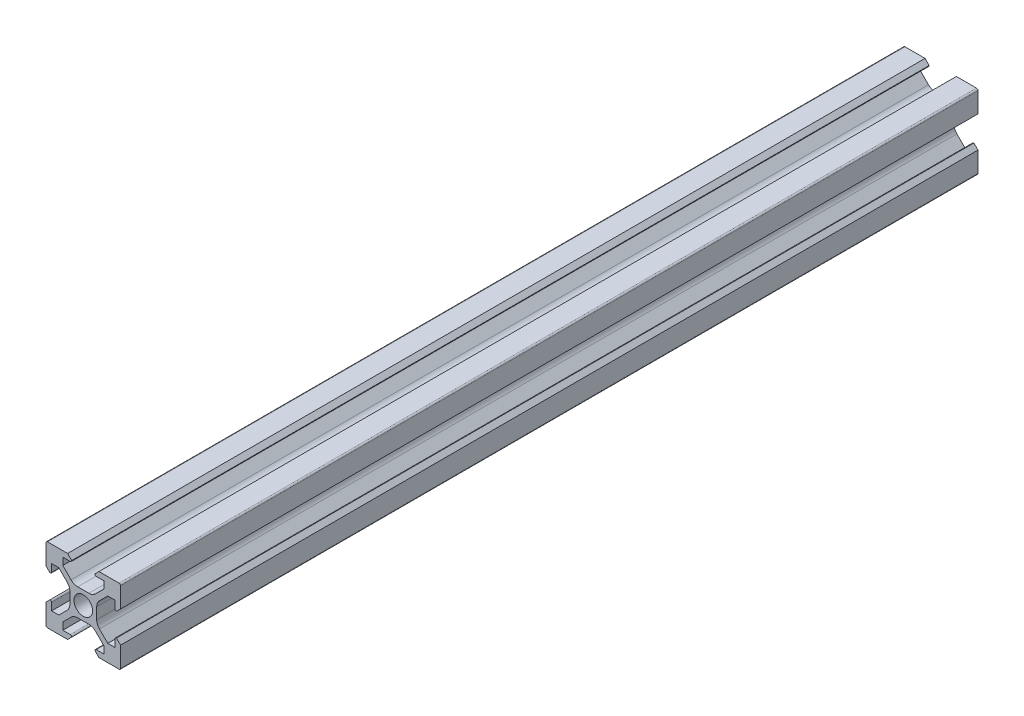
SolidWorks part; units mm, degrees
ref_plane "Plan de face" through (0, 0, 0) normal (0, 0, 1) x (1, 0, 0)
ref_plane "Plan de dessus" through (0, 0, 0) normal (0, 1, 0) x (1, 0, 0)
ref_plane "Plan de droite" through (0, 0, 0) normal (1, 0, 0) x (0, 0, -1)
sketch "Esquisse1" plane through (0, 0, 0) normal (0, 0, 1) x (1, 0, 0)
  line L0 (-3.1, 8.9) -> (-4.2, 10)
  line L1 (-9.6, 10) -> (-4.2, 10)
  line L2 (-3.6, 1.5038) -> (-3.6, 0)
  line L3 (-8.5, 5.5) -> (-8.5, 3.5)
  line L4 (-6.5607, 5.5) -> (-4.3322, 3.2716)
  line L5 (-8.5, 5.5) -> (-6.5607, 5.5)
  line L6 (-10, 9.6) -> (-10, 4.2)
  line L7 (-8.9, 3.1) -> (-10, 4.2)
  line L8 (0, 3.6) -> (0, -3.6) construction
  line L9 (9.8828, -9.8828) -> (0, 0) construction
  line L10 (9.8828, 9.8828) -> (0, 0) construction
  line L11 (3.6, -1.5038) -> (3.6, 0)
  line L12 (8.5, -5.5) -> (8.5, -3.5)
  line L13 (-5.5, 8.5) -> (-5.5, 6.5607)
  line L14 (6.5607, -5.5) -> (4.3322, -3.2716)
  line L15 (8.5, -5.5) -> (6.5607, -5.5)
  line L16 (3.1, -8.9) -> (4.2, -10)
  line L17 (9.6, -10) -> (4.2, -10)
  line L18 (5.5, -8.5) -> (5.5, -6.5607)
  line L19 (5.5, -6.5607) -> (3.2716, -4.3322)
  line L20 (5.5, -8.5) -> (3.5, -8.5)
  line L21 (10, -9.6) -> (10, -4.2)
  line L22 (-9.8828, 9.8828) -> (0, 0) construction
  line L23 (8.9, -3.1) -> (10, -4.2)
  line L24 (-5.5, 6.5607) -> (-3.2716, 4.3322)
  line L25 (5.5, 8.5) -> (3.5, 8.5)
  line L26 (5.5, 6.5607) -> (3.2716, 4.3322)
  line L27 (5.5, 8.5) -> (5.5, 6.5607)
  line L28 (8.9, 3.1) -> (10, 4.2)
  line L29 (10, 9.6) -> (10, 4.2)
  line L30 (8.5, 5.5) -> (6.5607, 5.5)
  line L31 (-5.5, 8.5) -> (-3.5, 8.5)
  line L32 (6.5607, 5.5) -> (4.3322, 3.2716)
  line L33 (8.5, 5.5) -> (8.5, 3.5)
  line L34 (3.6, 1.5038) -> (3.6, 0)
  line L35 (9.6, 10) -> (4.2, 10)
  line L36 (-1.5038, 3.6) -> (1.5038, 3.6)
  line L37 (3.1, 8.9) -> (4.2, 10)
  line L38 (-8.9, -3.1) -> (-10, -4.2)
  line L39 (-10, -9.6) -> (-10, -4.2)
  line L40 (-1.5038, -3.6) -> (1.5038, -3.6)
  line L41 (-5.5, -8.5) -> (-3.5, -8.5)
  line L42 (-5.5, -6.5607) -> (-3.2716, -4.3322)
  line L43 (-5.5, -8.5) -> (-5.5, -6.5607)
  line L44 (-9.6, -10) -> (-4.2, -10)
  line L45 (-3.1, -8.9) -> (-4.2, -10)
  line L46 (-8.5, -5.5) -> (-6.5607, -5.5)
  line L47 (-6.5607, -5.5) -> (-4.3322, -3.2716)
  line L48 (-8.5, -5.5) -> (-8.5, -3.5)
  line L49 (-3.6, -1.5038) -> (-3.6, 0)
  line L50 (-9.8828, -9.8828) -> (0, 0) construction
  arc A0 (2.5, 0) -> (-2.5, 0) centre (0, 0) ccw
  arc A1 (-3.5, 8.5) -> (-3.1, 8.9) centre (-3.5, 8.9) ccw
  arc A2 (-9.6, 10) -> (-10, 9.6) centre (-9.6, 9.6) ccw
  arc A3 (-3.2716, 4.3322) -> (-1.5038, 3.6) centre (-1.5038, 6.1) ccw
  arc A4 (-4.3322, 3.2716) -> (-3.6, 1.5038) centre (-6.1, 1.5038) cw
  arc A5 (-8.5, 3.5) -> (-8.9, 3.1) centre (-8.9, 3.5) cw
  arc A6 (3.5, -8.5) -> (3.1, -8.9) centre (3.5, -8.9) ccw
  arc A7 (3.2716, -4.3322) -> (1.5038, -3.6) centre (1.5038, -6.1) ccw
  arc A8 (4.3322, -3.2716) -> (3.6, -1.5038) centre (6.1, -1.5038) cw
  arc A9 (10, -9.6) -> (9.6, -10) centre (9.6, -9.6) cw
  arc A10 (8.5, -3.5) -> (8.9, -3.1) centre (8.9, -3.5) cw
  arc A11 (8.5, 3.5) -> (8.9, 3.1) centre (8.9, 3.5) ccw
  arc A12 (4.3322, 3.2716) -> (3.6, 1.5038) centre (6.1, 1.5038) ccw
  arc A13 (3.2716, 4.3322) -> (1.5038, 3.6) centre (1.5038, 6.1) cw
  arc A14 (9.6, 10) -> (10, 9.6) centre (9.6, 9.6) cw
  arc A15 (3.5, 8.5) -> (3.1, 8.9) centre (3.5, 8.9) cw
  arc A16 (-2.5, 0) -> (2.5, 0) centre (0, 0) ccw
  arc A17 (-8.5, -3.5) -> (-8.9, -3.1) centre (-8.9, -3.5) ccw
  arc A18 (-10, -9.6) -> (-9.6, -10) centre (-9.6, -9.6) ccw
  arc A19 (-4.3322, -3.2716) -> (-3.6, -1.5038) centre (-6.1, -1.5038) ccw
  arc A20 (-3.2716, -4.3322) -> (-1.5038, -3.6) centre (-1.5038, -6.1) cw
  arc A21 (-3.5, -8.5) -> (-3.1, -8.9) centre (-3.5, -8.9) cw
  point P95 (0, 0)
  dimension "D2" = 0.4
  dimension "D1" = 45
  dimension "D3" = 20
extrude "Boss.-Extru.1" add sketch "Esquisse1" along normal blind 230
